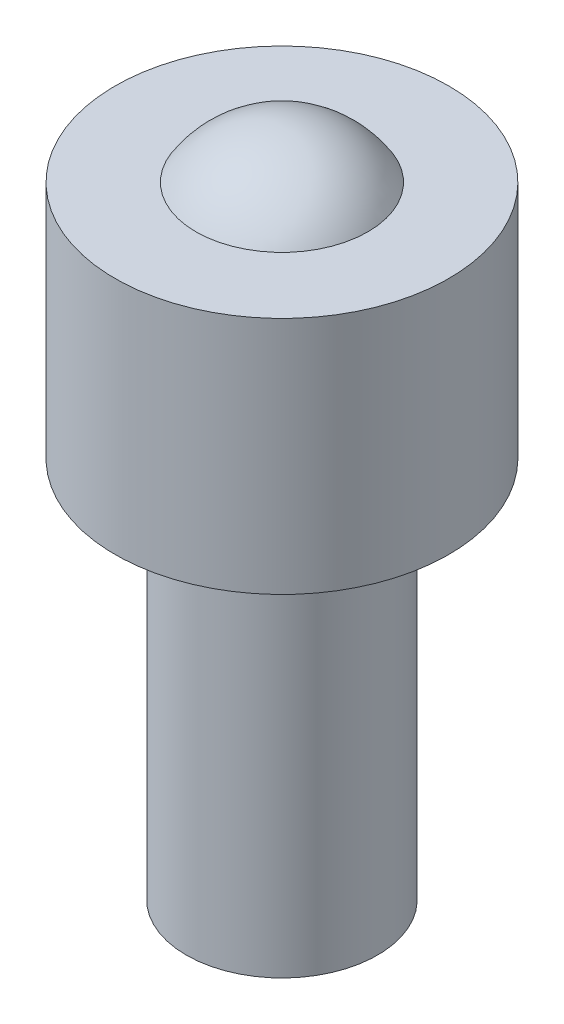
SolidWorks part; units mm, degrees
ref_plane "前视基准面" through (0, 0, 0) normal (0, 0, 1) x (1, 0, 0)
ref_plane "上视基准面" through (0, 0, 0) normal (0, 1, 0) x (1, 0, 0)
ref_plane "右视基准面" through (0, 0, 0) normal (1, 0, 0) x (0, 0, -1)
sketch "草图1" plane through (0, 0, 0) normal (0, 0, 1) x (1, 0, 0)
  line L0 (2.6972, 1.675) -> (5.2341, 1.675)
  line L1 (5.2341, 1.675) -> (5.2341, -5.825)
  line L2 (5.2341, -5.825) -> (3, -5.825)
  line L3 (3, -5.825) -> (3, -17.825)
  line L4 (3, -17.825) -> (0, -17.825)
  line L5 (0, -17.825) -> (0, 3.175)
  arc A0 (2.6972, 1.675) -> (0, 3.175) centre (0, 0) ccw
  dimension "D1" = 3.175
  dimension "D2" = 1.5
  dimension "D3" = 7.5
  dimension "D4" = 3
  dimension "D5" = 12
revolve "旋转1" add sketch "草图1" angle 360 about L5
